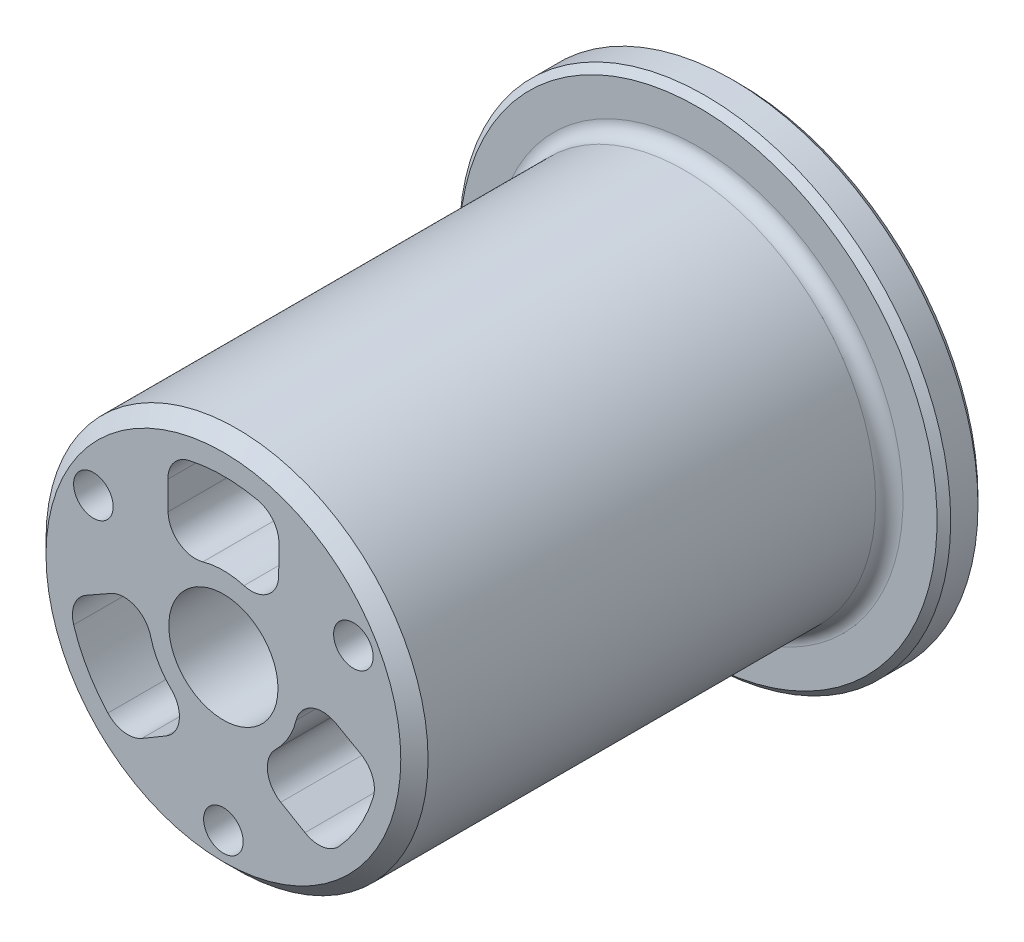
SolidWorks part; units mm, degrees
material "PA Tipo 6"
ref_plane "Alzado" through (0, 0, 0) normal (1, 0, 0) x (0, 1, 0)
ref_plane "Planta" through (0, 0, 0) normal (0, 0, 1) x (0, 1, 0)
ref_plane "Vista lateral" through (0, 0, 0) normal (0, 1, 0) x (-1, 0, 0)
sketch "Croquis1" plane through (0, 0, 0) normal (0, 0, 1) x (0, 1, 0)
  circle A0 centre (0, 0) radius 14
  circle A1 centre (0, 0) radius 4
  dimension "D1" = 28
  dimension "D2" = 8
extrude "Saliente-Extruir1" add sketch "Croquis1" along normal mid plane 37.8
chamfer "Chaflán1" distance 1 angle 45 1 edges at (14, 0, 18.9)
sketch "Croquis2" plane through (0, 0, 18.9) normal (0, 0, 1) x (1, 0, 0)
  line L0 (0, 5.5) -> (0, 13.4289) construction
  line L1 (4.0227, 3.7508) -> (4.0838, 10.7505)
  line L2 (-4.0227, 3.7508) -> (-4.0838, 10.7505)
  arc A0 (4.0227, 3.7508) -> (-4.0227, 3.7508) centre (0, 0) ccw
  arc A1 (4.0838, 10.7505) -> (-4.0838, 10.7505) centre (0, 0) ccw
  dimension "D1" = 5.5
  dimension "D2" = 11.5
  dimension "D3" = 0.5
  dimension "D4" = 7
extrude "Cortar-Extruir1" cut sketch "Croquis2" against normal up to next
fillet "Redondeo1" radius 2 4 edges at (4.0838, 10.7505, 0) (4.0227, 3.7508, 0) (-4.0227, 3.7508, 0) (-4.0838, 10.7505, 0)
pattern_circular "MatrizC1" count 3 every 120 about axis through (0, 0, 0) along (0, 0, 1) of "Cortar-Extruir1", "Redondeo1"
sketch "Croquis3" plane through (0, 0, 0) normal (0, 1, 0) x (-1, 0, 0)
  line L6 (-4, -18.9) -> (4, -18.9) construction
  line L7 (0, -18.9) -> (0, 18.9) construction
  line L8 (4, 18.9) -> (-4, 18.9) construction
  line L9 (-4, -0.4) -> (4, -0.4) construction
  circle A0 centre (0, -0.4) radius 4
  point P0 (0, -0.4)
  dimension "D2" = 8
  dimension "D1" = 18.5
extrude "Cortar-Extruir2" cut sketch "Croquis3" against normal blind 29
sketch "Croquis4" plane through (0, 0, 18.9) normal (0, 0, 1) x (1, 0, 0)
  line L0 (0, 0) -> (-15.604, 9.0089) construction
  line L1 (0, 0) -> (0, 13) construction
  circle A0 centre (0, 0) radius 13 construction
  circle A1 centre (0, 0) radius 11 construction
  point P3 (-9.5263, 5.5)
  point P12 (9.5263, 5.5)
  point P13 (0, -11)
  point P14 (0, 0)
  dimension "D2" = 22
  dimension "D1" = 60
  dimension "D3" = 3
hole_wizard "Taladro roscado M3.5x0.61" positions "Croquis4" profile "Croquis5" tap size "M3.5x0.6" standard "Ansi Metric"
sketch "Croquis5" plane through (0, 0, 18.9) normal (1, 0, 0) x (0, -1, 0)
  line L0 (0, 0) -> (0, 20.8712)
  line L1 (0, 20.8712) -> (1.45, 20)
  line L2 (1.45, 20) -> (1.45, 0)
  line L5 (1.45, 0) -> (0, 0)
  line L10 (0, 20.8712) -> (-1.45, 20) construction
  line L11 (0, -6.35) -> (0, 107.95) construction
  dimension "Diámetro de perforador para roscar" = 2.9
  dimension "Profundidad de perforador para roscar" = 20
  dimension "Ángulo de perforador" = 118
cosmetic thread "Rosca de taladro1" parameters "D1"=7, "D2"=3.5
cosmetic thread "Rosca de taladro2" parameters "D1"=7, "D2"=3.5
cosmetic thread "Rosca de taladro3" parameters "D1"=7, "D2"=3.5
sketch "Croquis6" plane through (0, 0, -18.9) normal (0, 0, -1) x (1, 0, 0)
  line L0 (-10.0496, 1.1017) -> (-8.2584, 0.0883) construction
  line L1 (-4.2057, 7.1078) -> (-5.9789, 8.1524) construction
  line L2 (5.9789, 8.1524) -> (4.2057, 7.1078) construction
  line L3 (8.2584, 0.0883) -> (10.0496, 1.1017) construction
  line L4 (-4.0527, -7.1961) -> (-4.0707, -9.2541) construction
  line L5 (4.0707, -9.2541) -> (4.0527, -7.1961) construction
  line L6 (-10.0496, 1.1017) -> (-8.2584, 0.0883)
  line L7 (-4.2057, 7.1078) -> (-5.9789, 8.1524)
  line L8 (5.9789, 8.1524) -> (4.2057, 7.1078)
  line L9 (8.2584, 0.0883) -> (10.0496, 1.1017)
  line L10 (-4.0527, -7.1961) -> (-4.0707, -9.2541)
  line L11 (4.0707, -9.2541) -> (4.0527, -7.1961)
  arc A0 (-10.9732, 3.4409) -> (-10.0496, 1.1017) centre (-9.0648, 2.8424) ccw construction
  arc A1 (-8.4665, 7.7826) -> (-10.9732, 3.4409) centre (0, 0) ccw construction
  arc A2 (-5.9789, 8.1524) -> (-8.4665, 7.7826) centre (-6.994, 6.4291) ccw construction
  arc A3 (-3.8286, 3.9487) -> (-5.3339, 1.3413) centre (0, 0) ccw construction
  arc A4 (-3.8286, 3.9487) -> (-4.2057, 7.1078) centre (-5.2208, 5.3846) ccw construction
  arc A5 (8.4665, 7.7826) -> (5.9789, 8.1524) centre (6.994, 6.4291) ccw construction
  arc A6 (10.9732, 3.4409) -> (8.4665, 7.7826) centre (0, 0) ccw construction
  arc A7 (10.0496, 1.1017) -> (10.9732, 3.4409) centre (9.0648, 2.8424) ccw construction
  arc A8 (-2.5067, -11.2235) -> (2.5067, -11.2235) centre (0, 0) ccw construction
  arc A9 (2.5067, -11.2235) -> (4.0707, -9.2541) centre (2.0708, -9.2716) ccw construction
  arc A10 (-4.0707, -9.2541) -> (-2.5067, -11.2235) centre (-2.0708, -9.2716) ccw construction
  arc A11 (4.0527, -7.1961) -> (1.5054, -5.29) centre (2.0528, -7.2136) ccw construction
  arc A12 (-1.5054, -5.29) -> (1.5054, -5.29) centre (0, 0) ccw construction
  arc A13 (5.3339, 1.3413) -> (8.2584, 0.0883) centre (7.2736, 1.829) ccw construction
  arc A14 (5.3339, 1.3413) -> (3.8286, 3.9487) centre (0, 0) ccw construction
  arc A15 (4.2057, 7.1078) -> (3.8286, 3.9487) centre (5.2208, 5.3846) ccw construction
  arc A16 (-8.2584, 0.0883) -> (-5.3339, 1.3413) centre (-7.2736, 1.829) ccw construction
  arc A17 (-1.5054, -5.29) -> (-4.0527, -7.1961) centre (-2.0528, -7.2136) ccw construction
  circle A18 centre (0, 0) radius 4 construction
  arc A20 (-10.9732, 3.4409) -> (-10.0496, 1.1017) centre (-9.0648, 2.8424) ccw
  arc A21 (-8.4665, 7.7826) -> (-10.9732, 3.4409) centre (0, 0) ccw
  arc A22 (-5.9789, 8.1524) -> (-8.4665, 7.7826) centre (-6.994, 6.4291) ccw
  arc A23 (-3.8286, 3.9487) -> (-5.3339, 1.3413) centre (0, 0) ccw
  arc A24 (-3.8286, 3.9487) -> (-4.2057, 7.1078) centre (-5.2208, 5.3846) ccw
  arc A25 (8.4665, 7.7826) -> (5.9789, 8.1524) centre (6.994, 6.4291) ccw
  arc A26 (10.9732, 3.4409) -> (8.4665, 7.7826) centre (0, 0) ccw
  arc A27 (10.0496, 1.1017) -> (10.9732, 3.4409) centre (9.0648, 2.8424) ccw
  arc A28 (-2.5067, -11.2235) -> (2.5067, -11.2235) centre (0, 0) ccw
  arc A29 (2.5067, -11.2235) -> (4.0707, -9.2541) centre (2.0708, -9.2716) ccw
  arc A30 (-4.0707, -9.2541) -> (-2.5067, -11.2235) centre (-2.0708, -9.2716) ccw
  arc A31 (4.0527, -7.1961) -> (1.5054, -5.29) centre (2.0528, -7.2136) ccw
  arc A32 (-1.5054, -5.29) -> (1.5054, -5.29) centre (0, 0) ccw
  arc A33 (5.3339, 1.3413) -> (8.2584, 0.0883) centre (7.2736, 1.829) ccw
  arc A34 (5.3339, 1.3413) -> (3.8286, 3.9487) centre (0, 0) ccw
  arc A35 (4.2057, 7.1078) -> (3.8286, 3.9487) centre (5.2208, 5.3846) ccw
  arc A36 (-8.2584, 0.0883) -> (-5.3339, 1.3413) centre (-7.2736, 1.829) ccw
  arc A37 (-1.5054, -5.29) -> (-4.0527, -7.1961) centre (-2.0528, -7.2136) ccw
  circle A38 centre (0, 0) radius 4
  circle A40 centre (0, 0) radius 18
  circle A41 centre (0, 0) radius 14 construction
  point P40 (0, 14)
  point P41 (0, 18)
  dimension "D1" = 4
extrude "Saliente-Extruir2" add sketch "Croquis6" against normal blind 3
chamfer "Chaflán2" distance 0.5 angle 45 2 edges at (-18, 0, -15.9) (-18, 0, -18.9)
fillet "Redondeo2" radius 1 1 edges at (-14, 0, -15.9)
sketch "Croquis10" plane through (0, 0, 18.9) normal (0, 0, 1) x (1, 0, 0)
  line L0 (0, 0) -> (0, 17.5) construction
  line L2 (-0.5, 14) -> (0.5, 14)
  line L3 (-0.5, 14) -> (-0.5, 13)
  line L4 (-0.5, 13) -> (0.5, 13)
  line L5 (0.5, 14) -> (0.5, 13)
  circle A0 centre (0, 0) radius 17.5 construction
  circle A1 centre (0, 0) radius 14 construction
  dimension "D1" = 1
  dimension "D2" = 1
